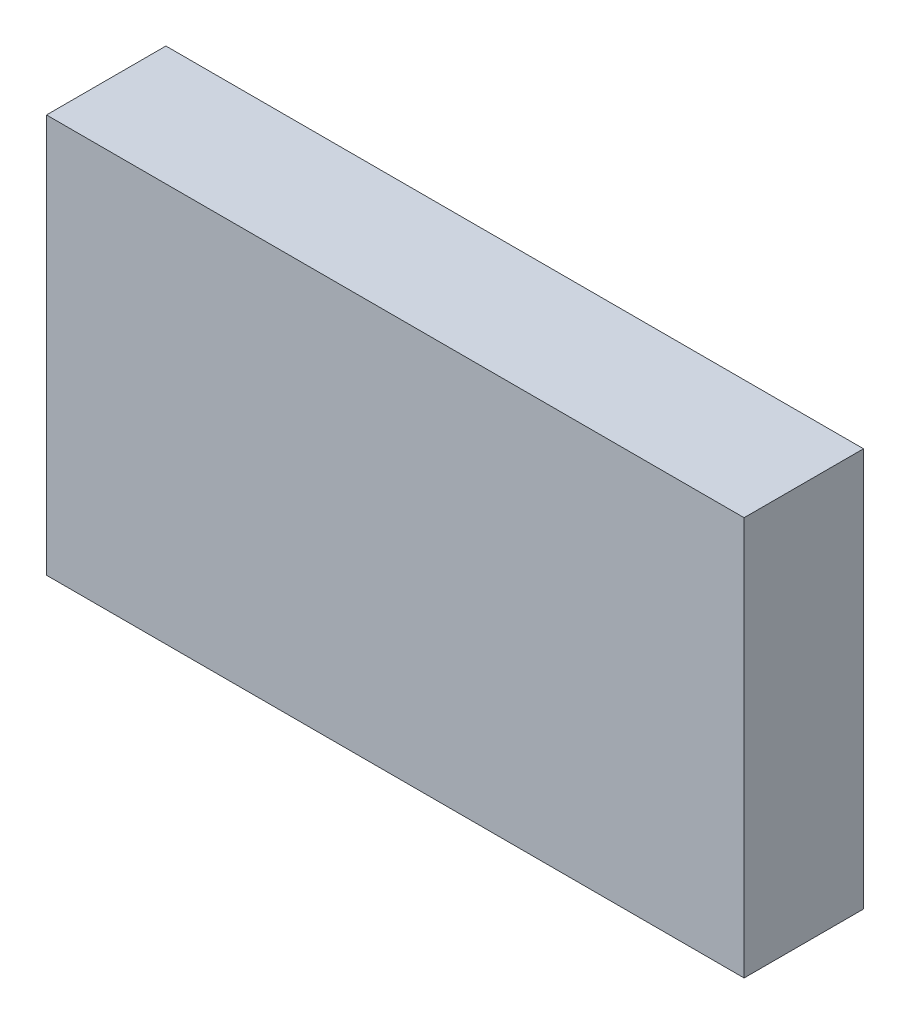
SolidWorks part; units mm, degrees
ref_plane "Спереди" through (0, 0, 0) normal (0, 0, 1) x (1, 0, 0)
ref_plane "Сверху" through (0, 0, 0) normal (0, 1, 0) x (1, 0, 0)
ref_plane "Справа" through (0, 0, 0) normal (1, 0, 0) x (0, 0, -1)
sketch "Эскиз1" plane through (0, 0, 0) normal (0, 0, 1) x (1, 0, 0)
  line L0 (29.2109, -16.6919) -> (-29.2109, -16.6919)
  line L1 (29.2109, -16.6919) -> (29.2109, 16.6919)
  line L2 (-29.2109, -16.6919) -> (-29.2109, 16.6919)
  line L3 (29.2109, 16.6919) -> (-29.2109, 16.6919)
  line L4 (29.2109, -16.6919) -> (-29.2109, 16.6919) construction
  line L5 (-29.2109, -16.6919) -> (29.2109, 16.6919) construction
  point P1 (0, 0)
extrude "Бобышка-Вытянуть1" add sketch "Эскиз1" along normal blind 10
